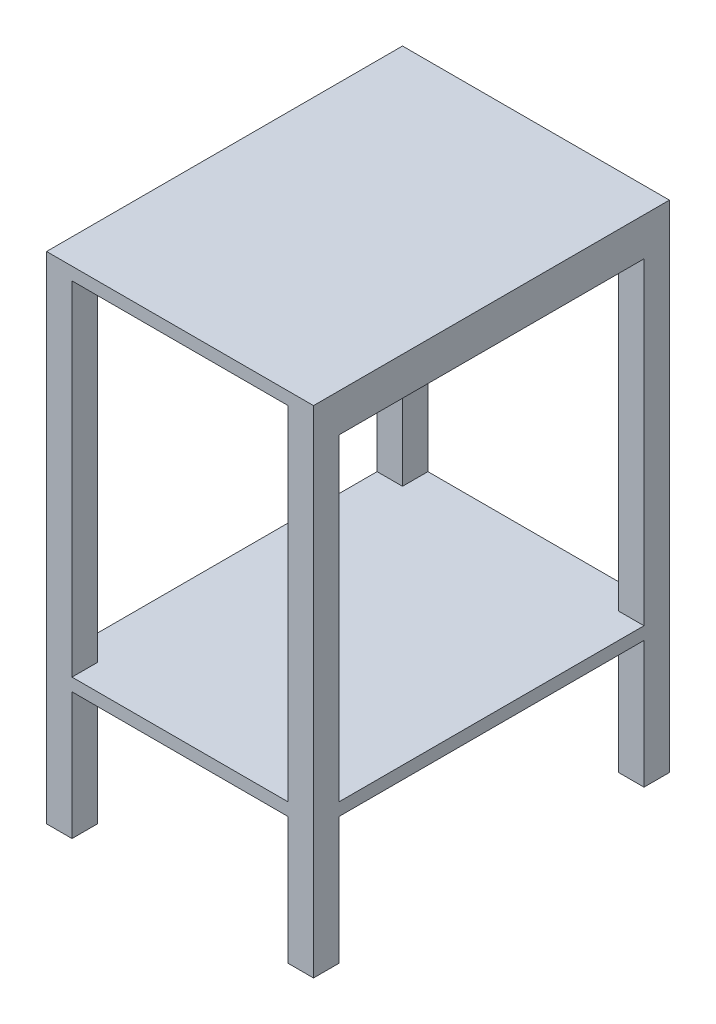
SolidWorks part; units mm, degrees
ref_plane "Front Plane" through (0, 0, 0) normal (0, 0, 1) x (1, 0, 0)
ref_plane "Top Plane" through (0, 0, 0) normal (0, 1, 0) x (1, 0, 0)
ref_plane "Right Plane" through (0, 0, 0) normal (1, 0, 0) x (0, 0, -1)
sketch "Sketch1" plane through (0, 0, 0) normal (0, 1, 0) x (1, 0, 0)
  line L1 (-105, -140) -> (105, -140)
  line L2 (-105, -140) -> (-105, 140)
  line L3 (-105, 140) -> (105, 140)
  line L4 (105, -140) -> (105, 140)
  line L5 (-105, -140) -> (105, 140) construction
  line L6 (-105, 140) -> (105, -140) construction
  point P0 (0, 0)
  dimension "D1" = 210
  dimension "D2" = 280
extrude "Boss-Extrude1" add sketch "Sketch1" along normal blind 390
sketch "Sketch4" plane through (105, 0, 0) normal (1, 0, 0) x (0, 0, -1)
  line L0 (0, 115.5) -> (0, -115.5) construction
  line L1 (-120, 0) -> (120, 0)
  line L2 (-120, 0) -> (-120, 100)
  line L3 (-120, 100) -> (120, 100)
  line L4 (120, 0) -> (120, 100)
  line L5 (-120, 0) -> (120, 100) construction
  line L6 (-120, 100) -> (120, 0) construction
  line L7 (115.5, 0) -> (-115.5, 0) construction
  line L8 (-120, 110) -> (120, 110)
  line L9 (-120, 110) -> (-120, 360)
  line L10 (-120, 360) -> (120, 360)
  line L11 (120, 110) -> (120, 360)
  line L12 (-120, 110) -> (120, 360) construction
  line L13 (-120, 360) -> (120, 110) construction
  line L14 (-140, 390) -> (-140, 0) construction
  line L15 (-140, 390) -> (140, 390) construction
  point P0 (0, 50)
  point P7 (0, 235)
  point P12 (-114.5694, 0)
  point P17 (0, 0)
  point P18 (-120, 110)
  dimension "D1" = 100
  dimension "D2" = 20
  dimension "D3" = 10
  dimension "D4" = 30
extrude "Cut-Extrude1" cut sketch "Sketch4" against normal blind 300
sketch "Sketch5" plane through (0, 0, 140) normal (0, 0, 1) x (1, 0, 0)
  line L0 (0, -154) -> (0, 154) construction
  line L1 (-85, 0) -> (85, 0)
  line L2 (-85, 0) -> (-85, 100)
  line L3 (-85, 100) -> (85, 100)
  line L4 (85, 0) -> (85, 100)
  line L5 (-85, 0) -> (85, 100) construction
  line L6 (-85, 100) -> (85, 0) construction
  line L7 (-105, 0) -> (105, 0) construction
  line L8 (-85, 110) -> (85, 110)
  line L9 (-85, 110) -> (-85, 380)
  line L10 (-85, 380) -> (85, 380)
  line L11 (85, 110) -> (85, 380)
  line L12 (-85, 110) -> (85, 380) construction
  line L13 (-85, 380) -> (85, 110) construction
  line L14 (-105, 390) -> (-105, 0) construction
  line L15 (-105, 390) -> (105, 390) construction
  point P0 (0, 50)
  point P7 (0, 245)
  point P12 (-75.2597, 173.6283)
  point P13 (-82.7463, 0)
  point P18 (-85, 170.082)
  dimension "D1" = 100
  dimension "D2" = 20
  dimension "D3" = 10
  dimension "D4" = 10
extrude "Cut-Extrude2" cut sketch "Sketch5" against normal blind 300
